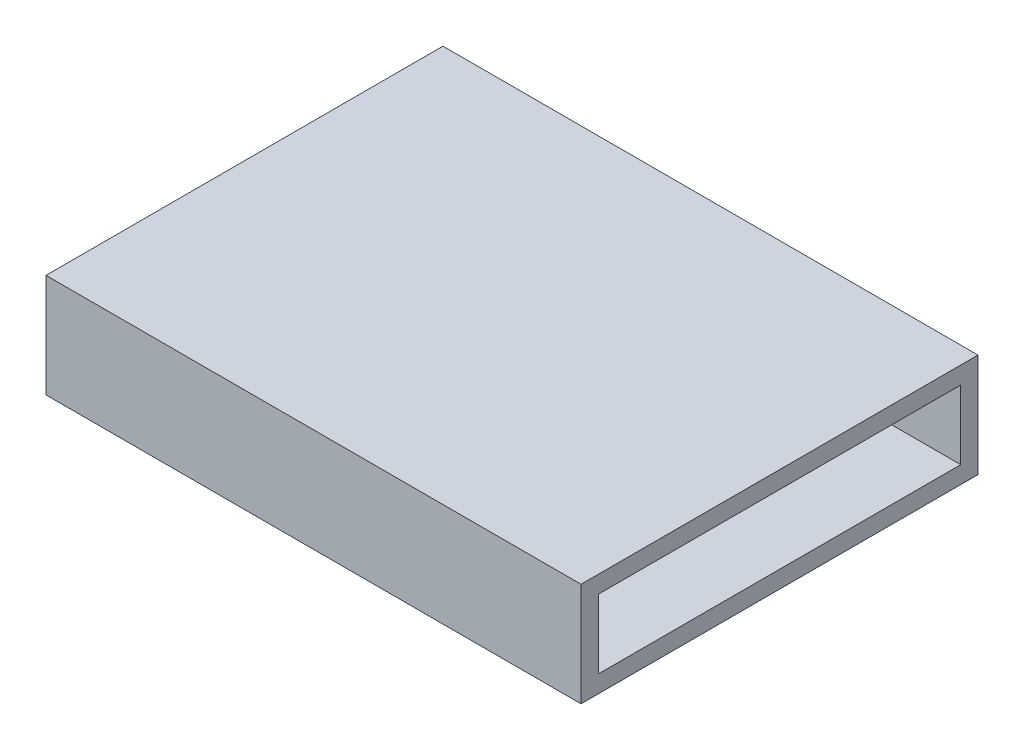
SolidWorks part; units mm, degrees
material "ABS"
ref_plane "Front Plane" through (0, 0, 0) normal (0, 0, 1) x (1, 0, 0)
ref_plane "Top Plane" through (0, 0, 0) normal (0, 1, 0) x (1, 0, 0)
ref_plane "Right Plane" through (0, 0, 0) normal (1, 0, 0) x (0, 0, -1)
sketch "Sketch1" plane through (0, 0, 0) normal (0, 1, 0) x (1, 0, 0)
  line L1 (0, 0) -> (155, 0)
  line L2 (0, 0) -> (0, 115)
  line L3 (0, 115) -> (155, 115)
  line L4 (155, 0) -> (155, 115)
  dimension "D1" = 115
  dimension "D2" = 155
extrude "Boss-Extrude1" add sketch "Sketch1" along normal blind 30
sketch "Sketch2" plane through (155, 0, 0) normal (1, 0, 0) x (0, 0, -1)
  line L14 (110, 5) -> (110, 25)
  line L15 (5, 5) -> (110, 5)
  line L16 (5, 25) -> (5, 5)
  line L17 (110, 25) -> (5, 25)
  line L18 (110, 5) -> (110, 25)
  line L19 (5, 5) -> (110, 5)
  line L20 (5, 25) -> (5, 5)
  line L21 (110, 25) -> (5, 25)
  dimension "D1" = 5
extrude "Cut-Extrude1" cut sketch "Sketch2" against normal through all
